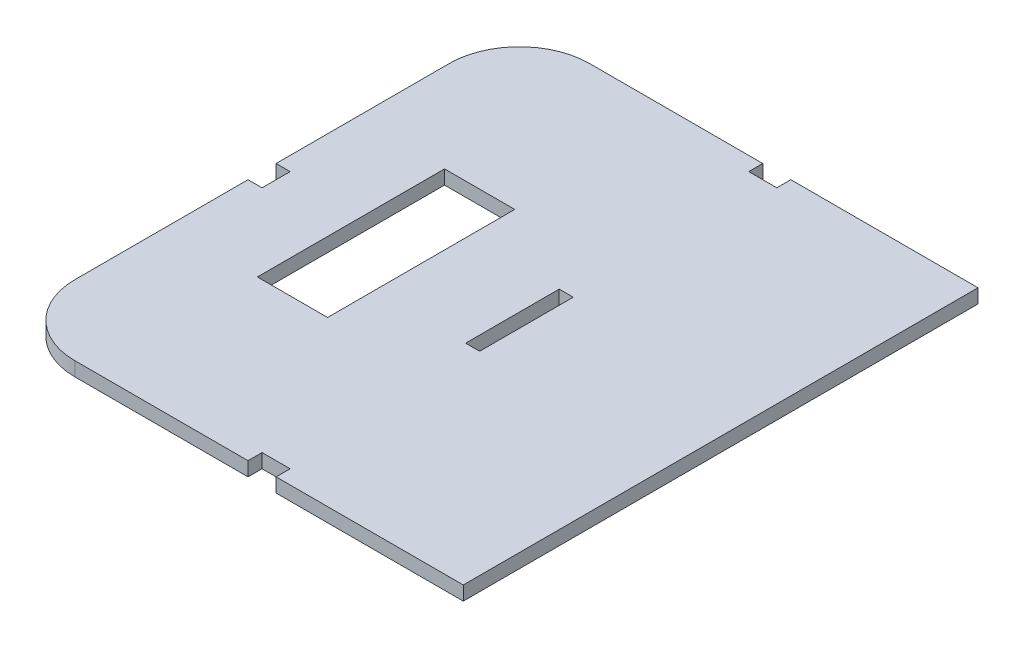
SolidWorks part; units mm, degrees
ref_plane "Спереди" through (0, 0, 0) normal (0, 0, 1) x (1, 0, 0)
ref_plane "Сверху" through (0, 0, 0) normal (0, 1, 0) x (1, 0, 0)
ref_plane "Справа" through (0, 0, 0) normal (1, 0, 0) x (0, 0, -1)
other "Configuration Table"
sketch "Эскиз4" plane through (0, 0, 0) normal (0, 1, 0) x (1, 0, 0)
  line L0 (98, 110) -> (98, 0)
  line L1 (0, 0) -> (52, 0)
  line L2 (0, 0) -> (0, 52)
  line L3 (0, 110) -> (52, 110)
  line L5 (58, 0) -> (98, 0)
  line L6 (55, 107) -> (52, 107)
  line L7 (52, 107) -> (55, 107)
  line L8 (55, 107) -> (58, 107)
  line L9 (52, 107) -> (52, 110)
  line L10 (58, 107) -> (58, 110)
  line L11 (58, 3) -> (58, 0)
  line L12 (55, 3) -> (58, 3)
  line L13 (55, 3) -> (52, 3)
  line L14 (52, 3) -> (52, 0)
  line L15 (3, 55) -> (3, 58)
  line L16 (3, 55) -> (3, 52)
  line L17 (3, 58) -> (0, 58)
  line L18 (3, 52) -> (0, 52)
  line L19 (55, 107) -> (55, 3) construction
  line L20 (3, 55) -> (55, 55) construction
  line L22 (0, 58) -> (0, 110)
  line L23 (58, 110) -> (98, 110)
  point P1 (58, 108.5)
  dimension "D1" = 55
  dimension "D2" = 110
  dimension "D3" = 3
  dimension "D4" = 3
  dimension "D5" = 6
  dimension "D6" = 3
  dimension "D7" = 3
  dimension "D8" = 3
  dimension "D9" = 3
  dimension "D10" = 3
  dimension "D11" = 3
  dimension "D12" = 3
  dimension "D13" = 40
extrude "Бобышка-Вытянуть3" add sketch "Эскиз4" along normal blind 3
sketch "Sketch1" plane through (0, 3, 0) normal (0, 1, 0) x (1, 0, 0)
  line L0 (3, 52) -> (3, 58) construction
  line L13 (3, 55) -> (107, 55) construction
  line L15 (55, 107) -> (55, 3) construction
  line L16 (52, 107) -> (58, 107) construction
  line L19 (19, 75) -> (34, 75)
  line L20 (19, 75) -> (19, 35)
  line L21 (19, 35) -> (34, 35)
  line L22 (34, 75) -> (34, 35)
  line L23 (53.5, 65) -> (56.5, 65)
  line L24 (53.5, 65) -> (53.5, 45)
  line L25 (53.5, 45) -> (56.5, 45)
  line L26 (56.5, 65) -> (56.5, 45)
  dimension "D1" = 3
  dimension "D2" = 20
  dimension "D3" = 16
  dimension "D4" = 15
  dimension "D5" = 40
extrude "Cut-Extrude1" cut sketch "Sketch1" against normal blind 10
fillet "Fillet1" radius 15 2 edges at (0, 1.5, 0) (0, 1.5, -110)
